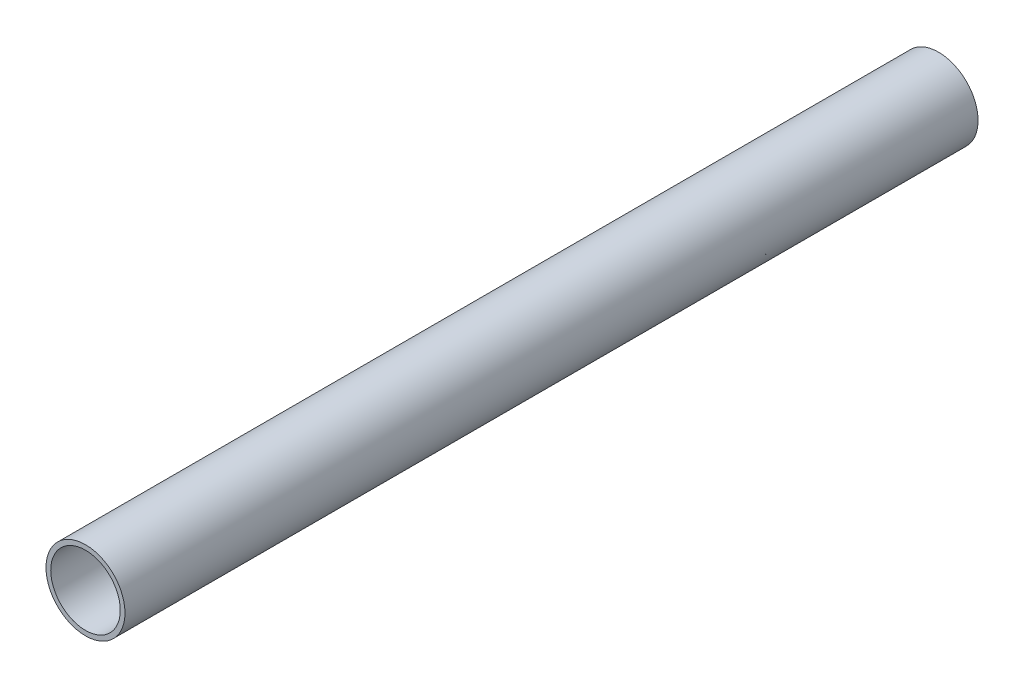
SolidWorks part; units mm, degrees
ref_plane "前视基准面" through (0, 0, 0) normal (0, 0, 1) x (1, 0, 0)
ref_plane "上视基准面" through (0, 0, 0) normal (0, 1, 0) x (1, 0, 0)
ref_plane "右视基准面" through (0, 0, 0) normal (1, 0, 0) x (0, 0, -1)
sketch "草图1" plane through (0, 0, 0) normal (0, 0, 1) x (1, 0, 0)
  circle A0 centre (0, 0) radius 12.5
extrude "凸台-拉伸2" add sketch "草图1" along normal blind 235.43 contours A0
sketch "草图2" plane through (0, 0, 0) normal (0, 0, -1) x (-1, 0, 0)
  circle A0 centre (0, 0) radius 9
extrude "切除-拉伸1" cut sketch "草图2" against normal blind 235.43
sketch "草图3" plane through (0, 0, 0) normal (0, 0, -1) x (-1, 0, 0)
  circle A0 centre (0, 0) radius 12.5
extrude "凸台-拉伸3" add sketch "草图3" along normal blind 15.57
sketch "草图4" plane through (0, 0, -15.57) normal (0, 0, -1) x (-1, 0, 0)
  circle A0 centre (0, 0) radius 9
extrude "切除-拉伸2" cut sketch "草图4" against normal blind 20
sketch "草图5" plane through (0, 0, -15.57) normal (0, 0, -1) x (-1, 0, 0)
  circle A0 centre (0, 0) radius 12.5
extrude "凸台-拉伸4" add sketch "草图5" along normal blind 9.93
sketch "草图6" plane through (0, 0, -25.5) normal (0, 0, -1) x (-1, 0, 0)
  circle A0 centre (0, 0) radius 9
extrude "切除-拉伸3" cut sketch "草图6" against normal blind 10
sketch "草图7" plane through (0, 0, -25.5) normal (0, 0, -1) x (-1, 0, 0)
  circle A0 centre (0, 0) radius 26.8585
extrude "切除-拉伸4" cut sketch "草图7" against normal blind 14.93
sketch "草图8" plane through (0, 0, -10.57) normal (0, 0, -1) x (-1, 0, 0)
  circle A0 centre (0, 0) radius 12.5
extrude "凸台-拉伸5" add sketch "草图8" along normal blind 9.93
sketch "草图9" plane through (0, 0, -20.5) normal (0, 0, -1) x (-1, 0, 0)
  circle A0 centre (0, 0) radius 9
extrude "切除-拉伸5" cut sketch "草图9" against normal blind 10
sketch "草图10" plane through (0, 0, -20.5) normal (0, 0, -1) x (-1, 0, 0)
  circle A0 centre (7.2017, 7.5079) radius 37.1934
extrude "切除-拉伸6" cut sketch "草图10" against normal blind 0.22
sketch "草图11" plane through (0, 0, -20.28) normal (0, 0, -1) x (-1, 0, 0)
  circle A0 centre (-1.2255, 2.3294) radius 43.1872
extrude "切除-拉伸7" cut sketch "草图11" against normal blind 0.71
sketch "草图12" plane through (0, 0, 235.43) normal (0, 0, 1) x (1, 0, 0)
  circle A0 centre (0, 0) radius 12.5
extrude "凸台-拉伸6" add sketch "草图12" along normal blind 15
sketch "草图13" plane through (0, 0, 250.43) normal (0, 0, 1) x (1, 0, 0)
  circle A0 centre (0, 0) radius 9
extrude "切除-拉伸8" cut sketch "草图13" against normal blind 15
sketch "草图14" plane through (0, 0, -19.57) normal (0, 0, -1) x (-1, 0, 0)
  circle A0 centre (0, 0) radius 11
extrude "切除-拉伸9" cut sketch "草图14" against normal blind 320
